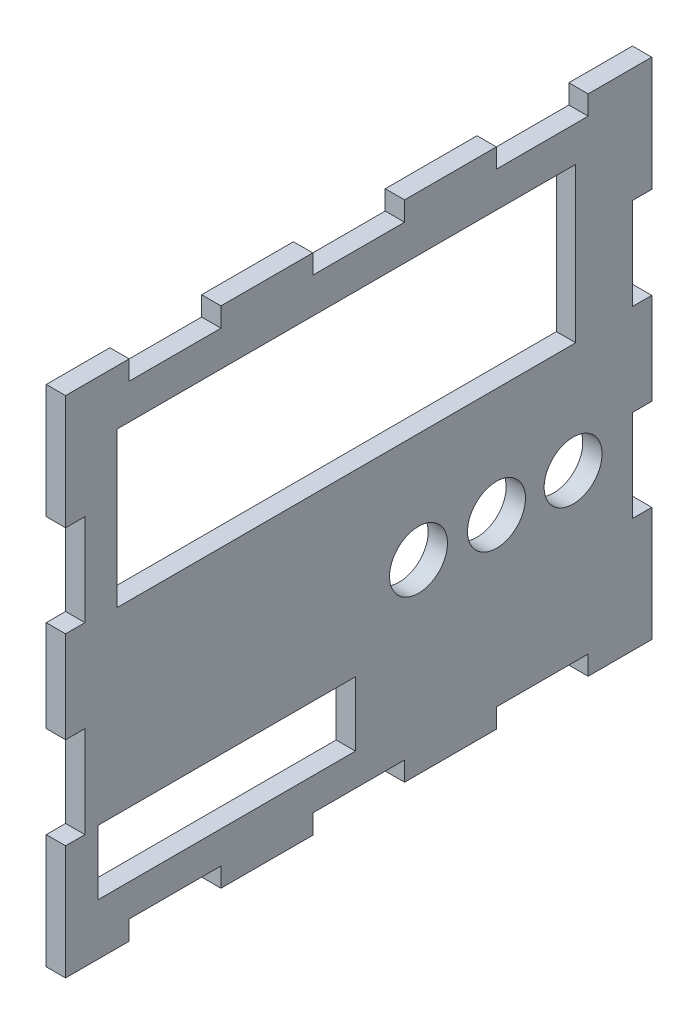
SolidWorks part; units mm, degrees
ref_plane "Front Plane" through (0, 0, 0) normal (0, 0, 1) x (1, 0, 0)
ref_plane "Top Plane" through (0, 0, 0) normal (0, 1, 0) x (1, 0, 0)
ref_plane "Right Plane" through (0, 0, 0) normal (1, 0, 0) x (0, 0, -1)
sketch "Sketch1" plane through (0, 0, 0) normal (1, 0, 0) x (0, 0, -1)
  line L148 (-46.8005, 37.0693) -> (-46.8005, 19.2943)
  line L149 (-46.8005, 19.2943) -> (-43.8005, 19.2943)
  line L150 (-43.8005, 19.2943) -> (-43.8005, 5.0443)
  line L151 (-43.8005, 5.0443) -> (-46.8005, 5.0443)
  line L152 (-46.8005, 5.0443) -> (-46.8005, -9.2057)
  line L153 (-46.8005, -9.2057) -> (-43.8005, -9.2057)
  line L154 (-43.8005, -9.2057) -> (-43.8005, -23.4557)
  line L155 (-43.8005, -23.4557) -> (-46.8005, -23.4557)
  line L156 (-46.8005, -23.4557) -> (-46.8005, -37.7057)
  line L157 (-46.8005, -37.7057) -> (-46.8005, -41.2307)
  line L158 (-46.8005, -41.2307) -> (-36.9255, -41.2307)
  line L159 (-36.9255, -41.2307) -> (-36.9255, -38.2307)
  line L160 (-36.9255, -38.2307) -> (-22.6755, -38.2307)
  line L161 (-22.6755, -38.2307) -> (-22.6755, -41.2307)
  line L162 (-22.6755, -41.2307) -> (-8.4255, -41.2307)
  line L163 (-8.4255, -41.2307) -> (-8.4255, -38.2307)
  line L164 (-8.4255, -38.2307) -> (5.8245, -38.2307)
  line L165 (5.8245, -38.2307) -> (5.8245, -41.2307)
  line L166 (5.8245, -41.2307) -> (20.0745, -41.2307)
  line L167 (20.0745, -41.2307) -> (20.0745, -38.2307)
  line L168 (20.0745, -38.2307) -> (34.3245, -38.2307)
  line L169 (34.3245, -38.2307) -> (34.3245, -41.2307)
  line L170 (34.3245, -41.2307) -> (44.1995, -41.2307)
  line L171 (44.1995, -41.2307) -> (44.1995, -23.4557)
  line L172 (44.1995, -23.4557) -> (41.1995, -23.4557)
  line L173 (41.1995, -23.4557) -> (41.1995, -9.2057)
  line L174 (41.1995, -9.2057) -> (44.1995, -9.2057)
  line L175 (44.1995, -9.2057) -> (44.1995, 5.0443)
  line L176 (44.1995, 5.0443) -> (41.1995, 5.0443)
  line L177 (41.1995, 5.0443) -> (41.1995, 19.2943)
  line L178 (41.1995, 19.2943) -> (44.1995, 19.2943)
  line L179 (44.1995, 19.2943) -> (44.1995, 33.5443)
  line L180 (44.1995, 33.5443) -> (44.1995, 37.0693)
  line L181 (44.1995, 37.0693) -> (34.3245, 37.0693)
  line L182 (34.3245, 37.0693) -> (34.3245, 34.0693)
  line L183 (34.3245, 34.0693) -> (20.0745, 34.0693)
  line L184 (20.0745, 34.0693) -> (20.0745, 37.0693)
  line L185 (20.0745, 37.0693) -> (5.8245, 37.0693)
  line L186 (5.8245, 37.0693) -> (5.8245, 34.0693)
  line L187 (5.8245, 34.0693) -> (-8.4255, 34.0693)
  line L188 (-8.4255, 34.0693) -> (-8.4255, 37.0693)
  line L189 (-8.4255, 37.0693) -> (-22.6755, 37.0693)
  line L190 (-22.6755, 37.0693) -> (-22.6755, 34.0693)
  line L191 (-22.6755, 34.0693) -> (-36.9255, 34.0693)
  line L192 (-36.9255, 34.0693) -> (-36.9255, 37.0693)
  line L193 (-36.9255, 37.0693) -> (-46.8005, 37.0693)
extrude "Boss-Extrude1" add sketch "Sketch1" along normal blind 3
sketch "Sketch2" plane through (3, 0, 0) normal (1, 0, 0) x (0, 0, -1)
  line L1 (-38.8005, 28.5693) -> (32.3995, 28.5693)
  line L2 (-38.8005, 28.5693) -> (-38.8005, 4.5693)
  line L3 (-38.8005, 4.5693) -> (32.3995, 4.5693)
  line L4 (32.3995, 28.5693) -> (32.3995, 4.5693)
  line L12 (41.1995, -23.4557) -> (41.1995, -9.2057) construction
  line L13 (-41.8005, -23.2307) -> (-1.8005, -23.2307)
  line L14 (-41.8005, -23.2307) -> (-41.8005, -33.2307)
  line L15 (-41.8005, -33.2307) -> (-1.8005, -33.2307)
  line L16 (-1.8005, -23.2307) -> (-1.8005, -33.2307)
  line L17 (-43.8005, -9.2057) -> (-43.8005, -23.4557) construction
  line L18 (-36.9255, -38.2307) -> (-22.6755, -38.2307) construction
  line L19 (2.1995, -6.8492) -> (37.9891, -6.8492) construction
  line L20 (2.1995, -6.8492) -> (2.1995, -17.9622) construction
  line L21 (-43.8005, 19.2943) -> (-43.8005, 5.0443) construction
  line L22 (34.3245, 34.0693) -> (20.0745, 34.0693) construction
  line L23 (2.1995, -17.9622) -> (37.9891, -17.9622) construction
  line L24 (37.9891, -6.8492) -> (37.9891, -17.9622) construction
  line L25 (41.1995, -9.2057) -> (44.1995, -9.2057) construction
  line L26 (31.9891, -12.4057) -> (7.9891, -12.4057) construction
  circle A3 centre (20.0943, -12.4057) radius 4.5
  circle A4 centre (7.9891, -12.4057) radius 4.5
  circle A5 centre (31.9891, -12.4057) radius 4.5
  point P26 (20.0943, -6.8492)
  point P27 (20.0943, -17.9622)
  point P33 (37.9891, -12.4057)
  dimension "D4" = 39
  dimension "D2" = 42
  dimension "D3" = 15
  dimension "D5" = 3.2
  dimension "D7" = 40
  dimension "D8" = 5
  dimension "D9" = 10
  dimension "D10" = 24
  dimension "D11" = 71.2
  dimension "D12" = 5.5
extrude "Cut-Extrude1" cut sketch "Sketch2" against normal blind 3
